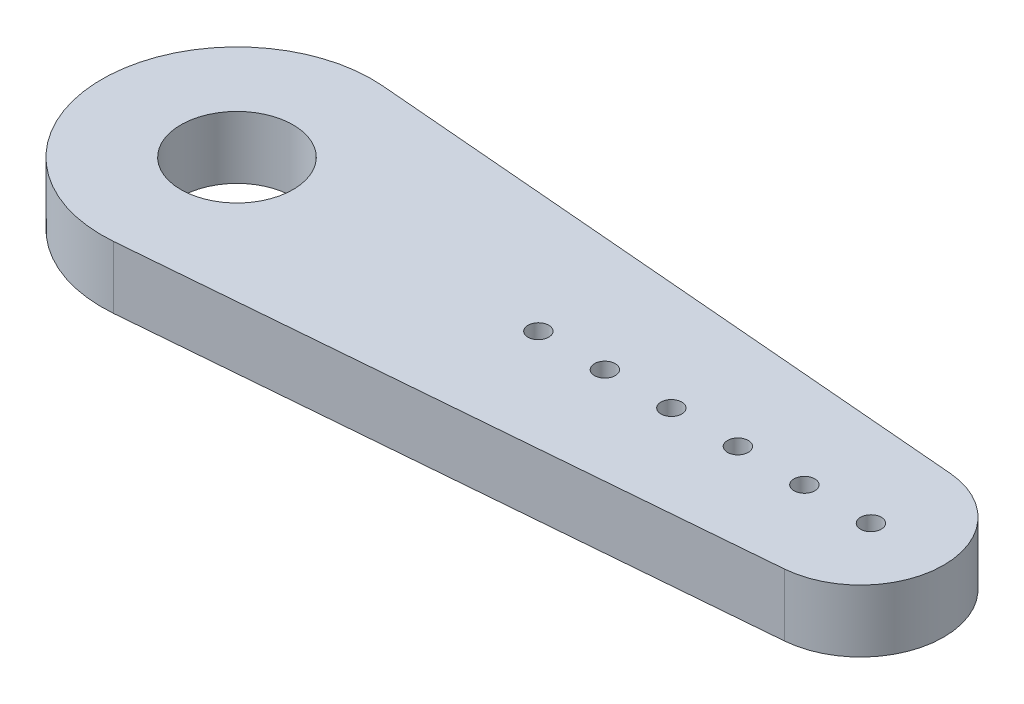
SolidWorks part; units mm, degrees
ref_plane "Front Plane" through (0, 0, 0) normal (0, 0, 1) x (1, 0, 0)
ref_plane "Top Plane" through (0, 0, 0) normal (0, 1, 0) x (1, 0, 0)
ref_plane "Right Plane" through (0, 0, 0) normal (1, 0, 0) x (0, 0, -1)
sketch "Sketch1" plane through (0, 0, 0) normal (0, 1, 0) x (1, 0, 0)
  line L0 (0.5417, 6.4774) -> (30.3333, 3.9861)
  line L1 (0.5417, -6.4774) -> (30.3333, -3.9861)
  arc A0 (0.5417, 6.4774) -> (0.5417, -6.4774) centre (0, 0) ccw
  arc A1 (30.3333, -3.9861) -> (30.3333, 3.9861) centre (30, 0) ccw
  circle A2 centre (30.5, 0) radius 0.5
  circle A3 centre (27.3, 0) radius 0.5
  circle A4 centre (24.1, 0) radius 0.5
  circle A5 centre (20.9, 0) radius 0.5
  circle A6 centre (17.7, 0) radius 0.5
  circle A7 centre (14.5, 0) radius 0.5
  circle A8 centre (0, 0) radius 2.7
  dimension "D1" = 13
  dimension "D2" = 8
  dimension "D5" = 1
  dimension "D11" = 5.4
  dimension "D3" = 30
  dimension "D4" = 30.5
  dimension "D6" = 14.5
  dimension "D7" = 17.7
  dimension "D8" = 20.9
  dimension "D9" = 24.1
  dimension "D10" = 27.3
extrude "Boss-Extrude2" add sketch "Sketch1" along normal blind 3
